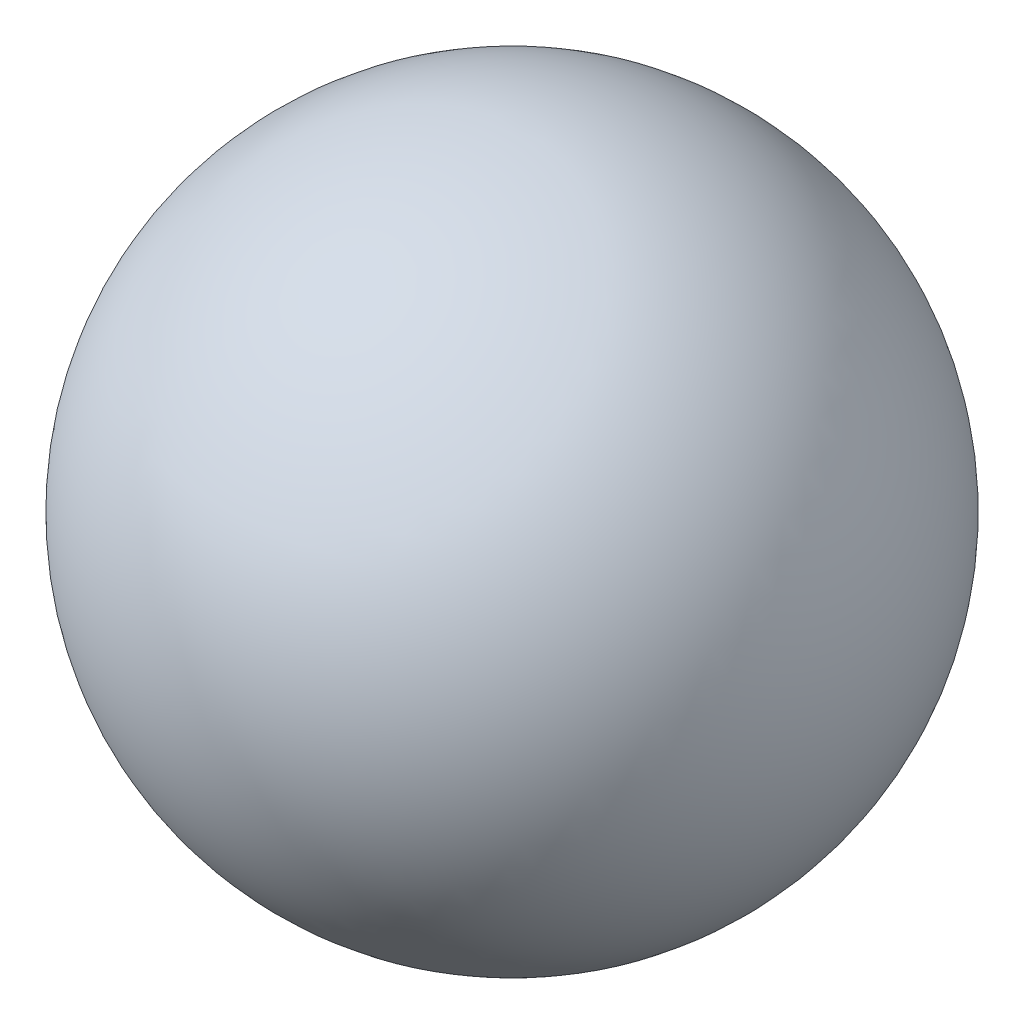
SolidWorks part; units mm, degrees
material "POLYURETHANE (11671)"
ref_plane "Front Plane" through (0, 0, 0) normal (0, 0, 1) x (1, 0, 0)
ref_plane "Top Plane" through (0, 0, 0) normal (0, 1, 0) x (1, 0, 0)
ref_plane "Right Plane" through (0, 0, 0) normal (1, 0, 0) x (0, 0, -1)
other "Center of Mass"
sketch "Sketch1" plane through (0, 0, 0) normal (0, 0, 1) x (1, 0, 0)
  line L0 (0, 165.1) -> (0, -165.1) construction
  line L2 (2.794, 162.2819) -> (2.794, -162.2819) construction
  line L3 (0, 165.1) -> (0, 162.306)
  line L4 (0, -165.1) -> (0, -162.306)
  arc A0 (0, -165.1) -> (0, 165.1) centre (0, 0) ccw
  arc A1 (0, -162.306) -> (0, 162.306) centre (0, 0) ccw
  arc A2 (2.794, -162.2819) -> (2.794, 162.2819) centre (0, 0) ccw construction
  dimension "D1" = 330.2
  dimension "D2" = 2.794
revolve "Revolve1" add sketch "Sketch1" angle 360 about L0
